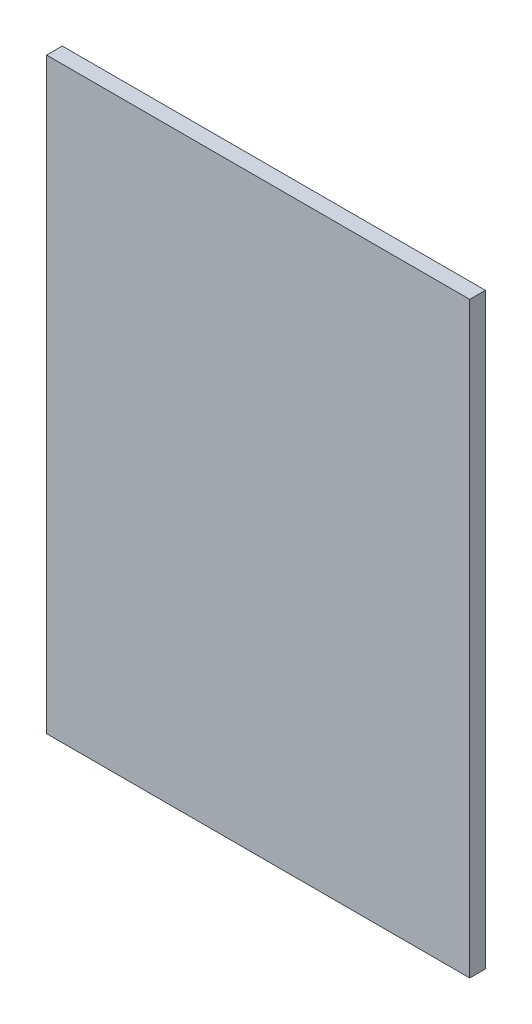
SolidWorks part; units mm, degrees
ref_plane "Front Plane" through (0, 0, 0) normal (0, 0, 1) x (1, 0, 0)
ref_plane "Top Plane" through (0, 0, 0) normal (0, 1, 0) x (1, 0, 0)
ref_plane "Right Plane" through (0, 0, 0) normal (1, 0, 0) x (0, 0, -1)
sketch "Sketch1" plane through (0, 0, 0) normal (0, 0, 1) x (1, 0, 0)
  line L1 (-47.6547, 112.0252) -> (60.3453, 112.0252)
  line L2 (-47.6547, 112.0252) -> (-47.6547, -37.9748)
  line L3 (-47.6547, -37.9748) -> (60.3453, -37.9748)
  line L4 (60.3453, 112.0252) -> (60.3453, -37.9748)
  dimension "D1" = 108
  dimension "D2" = 150
extrude "Boss-Extrude1" add sketch "Sketch1" along normal blind 4
